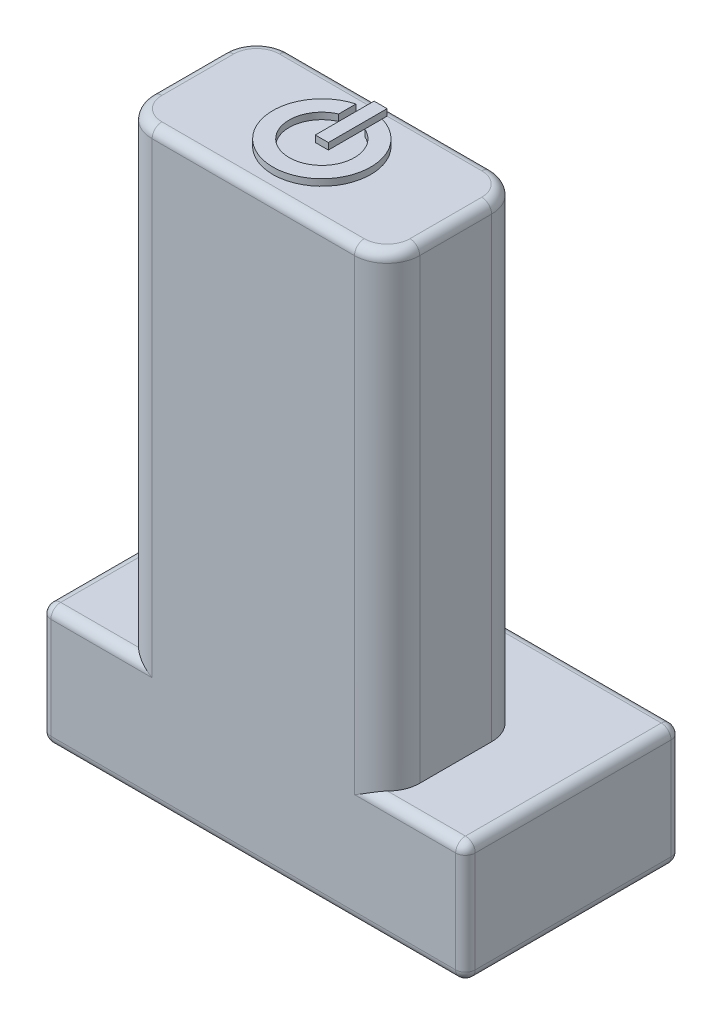
SolidWorks part; units mm, degrees
ref_plane "Front Plane" through (0, 0, 0) normal (0, 0, 1) x (1, 0, 0)
ref_plane "Top Plane" through (0, 0, 0) normal (0, 1, 0) x (1, 0, 0)
ref_plane "Right Plane" through (0, 0, 0) normal (1, 0, 0) x (0, 0, -1)
sketch "草图1" plane through (0, 0, 0) normal (0, 1, 0) x (1, 0, 0)
  line L8 (7.8943, 0.4) -> (16.0943, 0.4)
  line L9 (16.0943, 0.4) -> (16.0943, 4.6)
  line L10 (16.0943, 4.6) -> (7.8943, 4.6)
  line L11 (7.8943, 4.6) -> (7.8943, 0.4)
extrude "凸台-拉伸1" add sketch "草图1" along normal blind 18
sketch "草图2" plane through (0, 0, 0) normal (0, -1, 0) x (1, 0, 0)
  line L0 (5.4943, 2) -> (5.4943, -7)
  line L1 (5.4943, -7) -> (18.4943, -7)
  line L2 (18.4943, -7) -> (18.4943, 2)
  line L3 (18.4943, 2) -> (5.4943, 2)
  line L4 (7.8943, -0.4) -> (7.8943, -4.6)
  line L6 (7.8943, -0.4) -> (7.8943, -4.6)
  line L16 (7.8943, -4.6) -> (16.0943, -4.6)
  line L18 (7.8943, -4.6) -> (16.0943, -4.6)
  line L20 (16.0943, -4.6) -> (16.0943, -0.4)
  line L21 (16.0943, -4.6) -> (16.0943, -0.4)
  line L22 (16.0943, -0.4) -> (7.8943, -0.4)
  line L23 (16.0943, -0.4) -> (7.8943, -0.4)
  dimension "D1" = 0
extrude "凸台-拉伸2" add sketch "草图2" against normal blind 3.7
fillet "圆角1" radius 1 4 edges at (16.0943, 10.85, -4.6) (16.0943, 10.85, -0.4) (7.8943, 10.85, -4.6) (7.8943, 10.85, -0.4)
fillet "圆角2" radius 0.3 16 edges at (18.4943, 1.85, 2) (5.4943, 1.85, 2) (18.4943, 1.85, -7) (5.4943, 1.85, -7) (5.4943, 3.7, -2.5) (11.9943, 3.7, 2) (18.4943, 3.7, -2.5) (11.9943, 3.7, -7) (8.1872, 18, -0.6929) (7.8943, 18, -2.5) (8.1872, 18, -4.3071) (11.9943, 18, -4.6) (15.8014, 18, -4.3071) (16.0943, 18, -2.5) (15.8014, 18, -0.6929) (11.9943, 18, -0.4)
sketch "草图3" plane through (0, 18, 0) normal (0, 1, 0) x (1, 0, 0)
  line L0 (11.9943, 2.5) -> (12.1943, 2.5)
  line L1 (11.9943, 2.5) -> (11.7943, 2.5)
  line L2 (11.7943, 2.5) -> (11.7943, 4.3)
  line L3 (11.7943, 4.3) -> (12.1943, 4.3)
  line L4 (12.1943, 4.3) -> (12.1943, 2.5)
  line L6 (11.5943, 3.4165) -> (11.5943, 3.9457)
  line L8 (12.3943, 3.9457) -> (12.3943, 3.4165)
  arc A0 (11.5943, 3.9457) -> (12.3943, 3.9457) centre (11.9943, 2.5) ccw
  arc A1 (11.5943, 3.4165) -> (12.3943, 3.4165) centre (11.9943, 2.5) ccw
extrude "凸台-拉伸3" add sketch "草图3" along normal blind 0.2
sketch "草图4" plane through (0, 3.7, 0) normal (0, 1, 0) x (1, 0, 0)
  line L0 (11.9943, 0.4) -> (4.789, 0.4)
  line L1 (15.0943, 0.4) -> (8.8943, 0.4) construction
  line L2 (4.789, 0.4) -> (4.789, -2.3931)
  line L3 (4.789, -2.3931) -> (19.341, -2.3931)
  line L4 (19.341, -2.3931) -> (19.341, 0.4)
  line L5 (19.341, 0.4) -> (11.9943, 0.4)
extrude "切除-拉伸1" cut sketch "草图4" against normal blind 10
fillet "圆角3" radius 0.3 12 edges at (16.6443, 3.7, -0.4) (18.4065, 3.6121, -0.4) (7.3443, 3.7, -0.4) (5.5822, 3.6121, -0.4) (18.4943, 0, -3.55) (18.4065, 0, -6.9121) (11.9943, 0, -7) (5.5822, 0, -6.9121) (18.4943, 1.7, -0.4) (5.4943, 1.7, -0.4) (11.9943, 0, -0.4) (5.4943, 0, -3.55)
